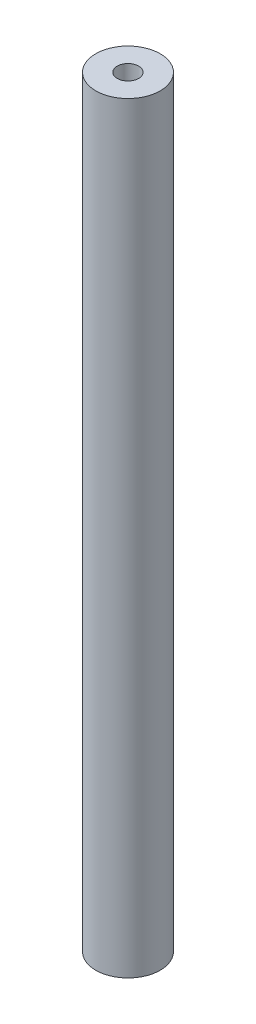
SolidWorks part; units mm, degrees
ref_plane "Front Plane" through (0, 0, 0) normal (0, 0, 1) x (1, 0, 0)
ref_plane "Top Plane" through (0, 0, 0) normal (0, 1, 0) x (1, 0, 0)
ref_plane "Right Plane" through (0, 0, 0) normal (1, 0, 0) x (0, 0, -1)
sketch "Sketch1" plane through (0, 0, 0) normal (0, 1, 0) x (1, 0, 0)
  circle A0 centre (0, 0) radius 3
extrude "Boss-Extrude1" add sketch "Sketch1" along normal blind 71
sketch "Sketch2" plane through (0, 71, 0) normal (0, 1, 0) x (1, 0, 0)
  circle A0 centre (0, 0) radius 1
extrude "Cut-Extrude1" cut sketch "Sketch2" against normal blind 3
sketch "Sketch3" plane through (0, 0, 0) normal (0, -1, 0) x (1, 0, 0)
  circle A0 centre (0, 0) radius 1
extrude "Cut-Extrude2" cut sketch "Sketch3" against normal blind 3
